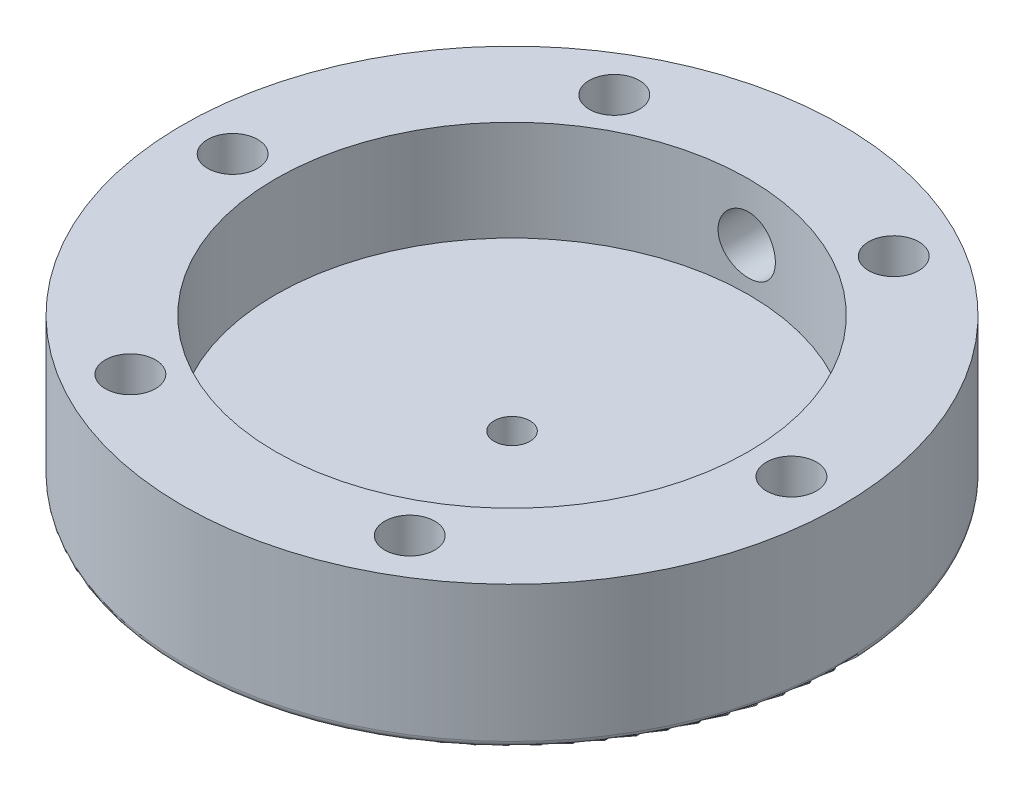
SolidWorks part; units mm, degrees
material "Gray Cast Iron"
ref_plane "Front Plane" through (0, 0, 0) normal (0, 0, 1) x (1, 0, 0)
ref_plane "Top Plane" through (0, 0, 0) normal (0, 1, 0) x (1, 0, 0)
ref_plane "Right Plane" through (0, 0, 0) normal (1, 0, 0) x (0, 0, -1)
sketch "Sketch1" plane through (0, 0, 0) normal (0, 1, 0) x (1, 0, 0)
  circle A0 centre (0, 0) radius 46
  dimension "D1" = 92
extrude "Boss-Extrude1" add sketch "Sketch1" along normal blind 20
sketch "Sketch2" plane through (0, 0, 0) normal (0, -1, 0) x (1, 0, 0)
  circle A0 centre (0, 0) radius 12
  dimension "D1" = 24
extrude "Boss-Extrude2" add sketch "Sketch2" along normal blind 10
sketch "Sketch3" plane through (0, 20, 0) normal (0, 1, 0) x (1, 0, 0)
  circle A0 centre (0, 0) radius 33
  dimension "D1" = 66
extrude "Cut-Extrude1" cut sketch "Sketch3" against normal blind 14
sketch "Sketch4" plane through (0, -10, 0) normal (0, -1, 0) x (1, 0, 0)
  circle A0 centre (0, 0) radius 2.5
  dimension "D1" = 5
extrude "Cut-Extrude2" cut sketch "Sketch4" against normal through all
sketch "Sketch5" plane through (0, 0, 0) normal (0, -1, 0) x (1, 0, 0)
  circle A0 centre (0, 0) radius 39 construction
  circle A1 centre (-39, 0) radius 3.5
  circle A2 centre (-19.5, 33.775) radius 3.5
  circle A3 centre (19.5, 33.775) radius 3.5
  circle A4 centre (39, 0) radius 3.5
  circle A5 centre (19.5, -33.775) radius 3.5
  circle A6 centre (-19.5, -33.775) radius 3.5
  point P17 (0, 0)
  dimension "D1" = 78
  dimension "D2" = 7
  dimension "D3" = 6
extrude "Cut-Extrude3" cut sketch "Sketch5" against normal through all
fillet "Fillet1" radius 1 1 edges at (0, 0, 46)
sketch "Sketch6" plane through (0, -10, 0) normal (0, -1, 0) x (1, 0, 0)
  circle A0 centre (0, 0) radius 7
  dimension "D1" = 14
extrude "Cut-Extrude4" cut sketch "Sketch6" against normal blind 10
chamfer "Chamfer1" distance 1 angle 45 1 edges at (0, -10, -7)
sketch "Sketch8" plane through (0, 0, 0) normal (0, 0, 1) x (1, 0, 0)
  line L0 (46, 20) -> (-46, 20) construction
  circle A0 centre (0, 12) radius 4
  dimension "D2" = 8
  dimension "D1" = 8
extrude "Cut-Extrude5" cut sketch "Sketch8" against normal blind 250
